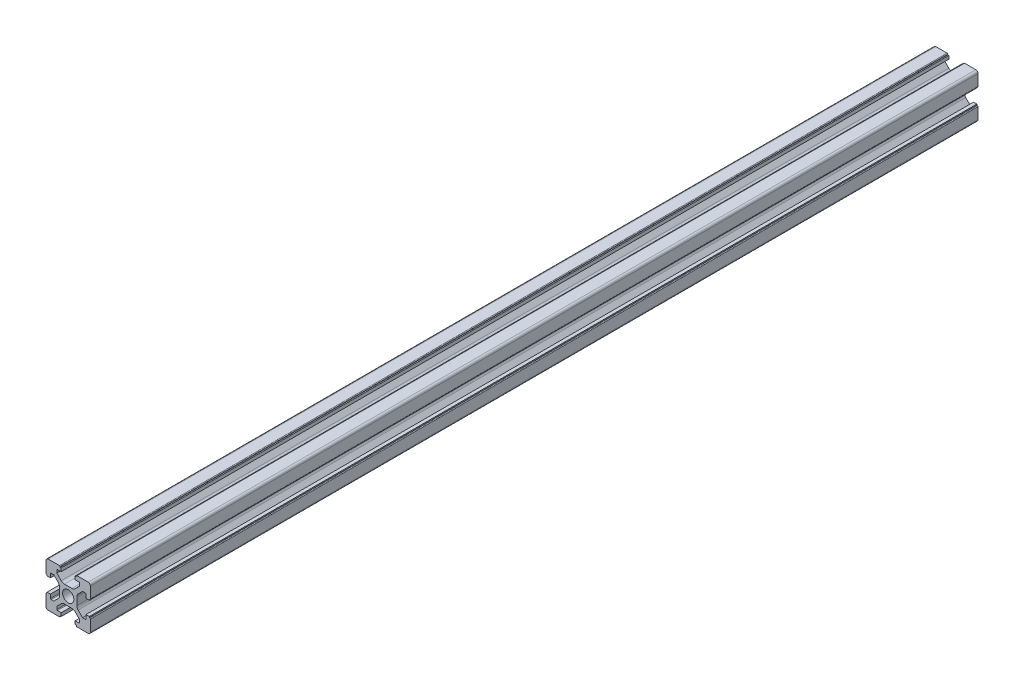
SolidWorks part; units mm, degrees
material "6063-T5"
ref_plane "Alzado" through (0, 0, 0) normal (0, 0, 1) x (1, 0, 0)
ref_plane "Planta" through (0, 0, 0) normal (0, 1, 0) x (1, 0, 0)
ref_plane "Vista lateral" through (0, 0, 0) normal (1, 0, 0) x (0, 0, -1)
sketch "Croquis1" plane through (0, 0, 0) normal (0, 0, 1) x (1, 0, 0)
  line L0 (-10, -9) -> (-10, -3.95)
  line L1 (-9.7, -3.65) -> (-9.5, -3.65)
  line L2 (-9.5, -3.65) -> (-9.5, -3.15)
  line L3 (-9.5, -3.15) -> (-8, -3.15)
  line L4 (-8, -3.15) -> (-8, -4.85)
  line L5 (-7.7, -5.15) -> (-6.5, -5.15)
  line L6 (-6.5, -5.15) -> (-4.4858, -3.1358)
  line L7 (-3.9, -1.7216) -> (-3.9, 1.7216)
  line L8 (-6.5, 5.15) -> (-4.4858, 3.1358)
  line L9 (-7.7, 5.15) -> (-6.5, 5.15)
  line L10 (-8, 3.15) -> (-8, 4.85)
  line L11 (-9.5, 3.15) -> (-8, 3.15)
  line L12 (-9.5, 3.65) -> (-9.5, 3.15)
  line L13 (-9.7, 3.65) -> (-9.5, 3.65)
  line L14 (-10, 9) -> (-10, 3.95)
  line L15 (-9, 10) -> (-3.95, 10)
  line L16 (-3.65, 9.7) -> (-3.65, 9.5)
  line L17 (-3.65, 9.5) -> (-3.15, 9.5)
  line L18 (-3.15, 9.5) -> (-3.15, 8)
  line L19 (-3.15, 8) -> (-4.85, 8)
  line L20 (-5.15, 7.7) -> (-5.15, 6.5)
  line L21 (-5.15, 6.5) -> (-3.1358, 4.4858)
  line L22 (1.7216, 3.9) -> (-1.7216, 3.9)
  line L23 (5.15, 6.5) -> (3.1358, 4.4858)
  line L24 (5.15, 7.7) -> (5.15, 6.5)
  line L25 (3.15, 8) -> (4.85, 8)
  line L26 (3.15, 9.5) -> (3.15, 8)
  line L27 (3.65, 9.5) -> (3.15, 9.5)
  line L28 (3.65, 9.7) -> (3.65, 9.5)
  line L29 (9, 10) -> (3.95, 10)
  line L30 (10, 9) -> (10, 3.95)
  line L31 (9.7, 3.65) -> (9.5, 3.65)
  line L32 (9.5, 3.65) -> (9.5, 3.15)
  line L33 (9.5, 3.15) -> (8, 3.15)
  line L34 (8, 3.15) -> (8, 4.85)
  line L35 (7.7, 5.15) -> (6.5, 5.15)
  line L36 (6.5, 5.15) -> (4.4858, 3.1358)
  line L37 (3.9, 1.7216) -> (3.9, -1.7216)
  line L38 (6.5, -5.15) -> (4.4858, -3.1358)
  line L39 (7.7, -5.15) -> (6.5, -5.15)
  line L40 (8, -3.15) -> (8, -4.85)
  line L41 (9.5, -3.15) -> (8, -3.15)
  line L42 (9.5, -3.65) -> (9.5, -3.15)
  line L43 (9.7, -3.65) -> (9.5, -3.65)
  line L44 (10, -9) -> (10, -3.95)
  line L45 (9, -10) -> (3.95, -10)
  line L46 (3.65, -9.7) -> (3.65, -9.5)
  line L47 (3.65, -9.5) -> (3.15, -9.5)
  line L48 (3.15, -9.5) -> (3.15, -8)
  line L49 (3.15, -8) -> (4.85, -8)
  line L50 (5.15, -7.7) -> (5.15, -6.5)
  line L51 (5.15, -6.5) -> (3.1358, -4.4858)
  line L52 (-1.7216, -3.9) -> (1.7216, -3.9)
  line L53 (-5.15, -6.5) -> (-3.1358, -4.4858)
  line L54 (-5.15, -7.7) -> (-5.15, -6.5)
  line L55 (-3.15, -8) -> (-4.85, -8)
  line L56 (-3.15, -9.5) -> (-3.15, -8)
  line L57 (-3.65, -9.5) -> (-3.15, -9.5)
  line L58 (-3.65, -9.7) -> (-3.65, -9.5)
  line L59 (-9, -10) -> (-3.95, -10)
  ellipse E0 centre (0, 0) end of major axis (2.55, 0) minor radius 2.55
  ellipse E1 centre (-9, -9) end of major axis (-10, -9) minor radius 1 (-10, -9) -> (-9, -10) ccw
  ellipse E2 centre (-9.7, -3.95) end of major axis (-10, -3.95) minor radius 0.3 (-9.7, -3.65) -> (-10, -3.95) ccw
  ellipse E3 centre (-7.7, -4.85) end of major axis (-7.4, -4.85) minor radius 0.3 (-8, -4.85) -> (-7.7, -5.15) ccw
  ellipse E4 centre (-5.9, -1.7216) end of major axis (-5.9, 0.2784) minor radius 2 (-4.4858, -3.1358) -> (-3.9, -1.7216) ccw
  ellipse E5 centre (-5.9, 1.7216) end of major axis (-7.9, 1.7216) minor radius 2 (-3.9, 1.7216) -> (-4.4858, 3.1358) ccw
  ellipse E6 centre (-7.7, 4.85) end of major axis (-7.4, 4.85) minor radius 0.3 (-7.7, 5.15) -> (-8, 4.85) ccw
  ellipse E7 centre (-9.7, 3.95) end of major axis (-9.4, 3.95) minor radius 0.3 (-10, 3.95) -> (-9.7, 3.65) ccw
  ellipse E8 centre (-9, 9) end of major axis (-10, 9) minor radius 1 (-9, 10) -> (-10, 9) ccw
  ellipse E9 centre (-3.95, 9.7) end of major axis (-3.65, 9.7) minor radius 0.3 (-3.65, 9.7) -> (-3.95, 10) ccw
  ellipse E10 centre (-4.85, 7.7) end of major axis (-4.55, 7.7) minor radius 0.3 (-4.85, 8) -> (-5.15, 7.7) ccw
  ellipse E11 centre (-1.7216, 5.9) end of major axis (-3.7216, 5.9) minor radius 2 (-3.1358, 4.4858) -> (-1.7216, 3.9) ccw
  ellipse E12 centre (1.7216, 5.9) end of major axis (-0.2784, 5.9) minor radius 2 (1.7216, 3.9) -> (3.1358, 4.4858) ccw
  ellipse E13 centre (4.85, 7.7) end of major axis (4.85, 8) minor radius 0.3 (5.15, 7.7) -> (4.85, 8) ccw
  ellipse E14 centre (3.95, 9.7) end of major axis (3.95, 9.4) minor radius 0.3 (3.95, 10) -> (3.65, 9.7) ccw
  ellipse E15 centre (9, 9) end of major axis (10, 9) minor radius 1 (10, 9) -> (9, 10) ccw
  ellipse E16 centre (9.7, 3.95) end of major axis (10, 3.95) minor radius 0.3 (9.7, 3.65) -> (10, 3.95) ccw
  ellipse E17 centre (7.7, 4.85) end of major axis (8, 4.85) minor radius 0.3 (8, 4.85) -> (7.7, 5.15) ccw
  ellipse E18 centre (5.9, 1.7216) end of major axis (7.9, 1.7216) minor radius 2 (4.4858, 3.1358) -> (3.9, 1.7216) ccw
  ellipse E19 centre (5.9, -1.7216) end of major axis (7.9, -1.7216) minor radius 2 (3.9, -1.7216) -> (4.4858, -3.1358) ccw
  ellipse E20 centre (7.7, -4.85) end of major axis (8, -4.85) minor radius 0.3 (7.7, -5.15) -> (8, -4.85) ccw
  ellipse E21 centre (9.7, -3.95) end of major axis (10, -3.95) minor radius 0.3 (10, -3.95) -> (9.7, -3.65) ccw
  ellipse E22 centre (9, -9) end of major axis (10, -9) minor radius 1 (9, -10) -> (10, -9) ccw
  ellipse E23 centre (3.95, -9.7) end of major axis (3.95, -9.4) minor radius 0.3 (3.65, -9.7) -> (3.95, -10) ccw
  ellipse E24 centre (4.85, -7.7) end of major axis (4.85, -7.4) minor radius 0.3 (4.85, -8) -> (5.15, -7.7) ccw
  ellipse E25 centre (1.7216, -5.9) end of major axis (1.7216, -3.9) minor radius 2 (3.1358, -4.4858) -> (1.7216, -3.9) ccw
  ellipse E26 centre (-1.7216, -5.9) end of major axis (-1.7216, -3.9) minor radius 2 (-1.7216, -3.9) -> (-3.1358, -4.4858) ccw
  ellipse E27 centre (-4.85, -7.7) end of major axis (-4.55, -7.7) minor radius 0.3 (-5.15, -7.7) -> (-4.85, -8) ccw
  ellipse E28 centre (-3.95, -9.7) end of major axis (-3.65, -9.7) minor radius 0.3 (-3.95, -10) -> (-3.65, -9.7) ccw
  dimension "D1" = 20
extrude "Saliente-Extruir1" add sketch "Croquis1" along normal blind 400 contours E0 | L15 E9 L16 L17 L18 L19 E10 L20 L21 E11 L22 E12 L23 L24 E13 L25 L26 L27 L28 E14 L29 E15 L30 E16 L31 L32 L33 L34 E17 L35 L36 E18 L37 E19 L38 L39 E20 L40 L41 L42 L43 E21 L44 E22 L45 E23 L46 L47 L48 L49 E24 L50 L51 E25 L52 E26 L53 L54 E27 L55 L56 L57 L58 E28 L59 E1 L0 E2 L1 L2 L3 L4 E3 L5 L6 E4 L7 E5 L8 L9 E6 L10 L11 L12 L13 E7 L14 E8
